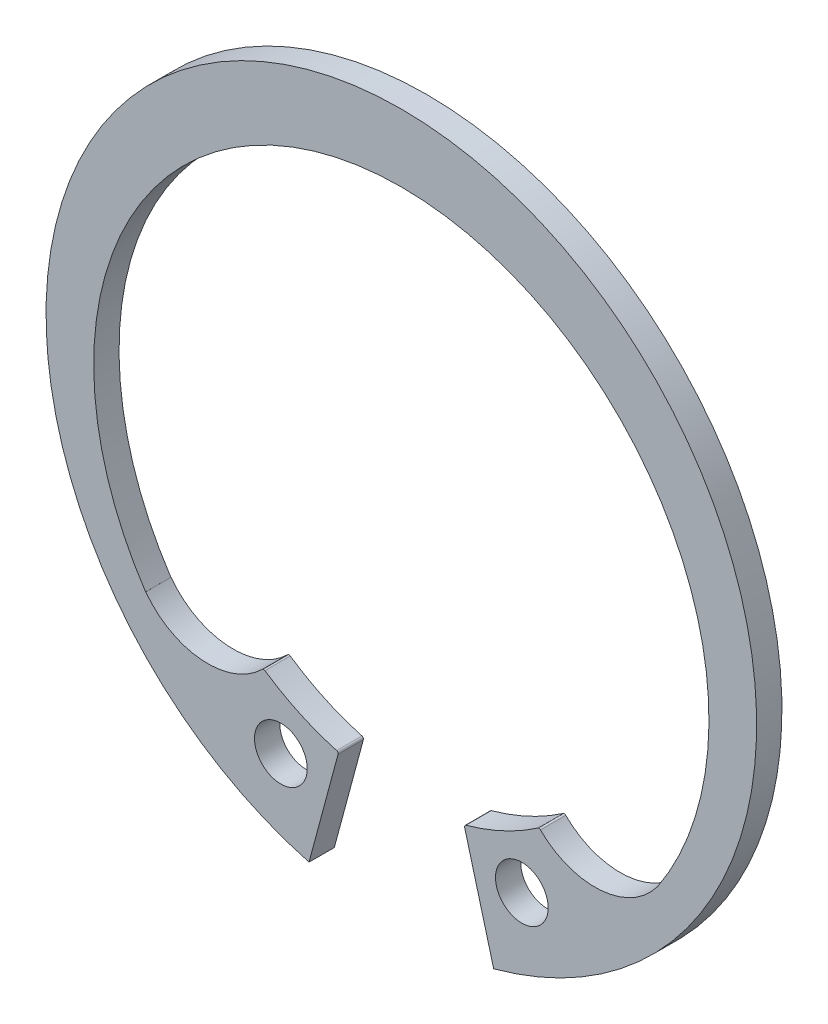
SolidWorks part; units mm, degrees
extrude "Body" add sketch "BodySke" against normal blind 1.2
sketch "BodySke" plane through (0, 0, 0) normal (0, 0, 1) x (1, 0, 0)
  line L0 (-1.5431, 0) -> (1.5431, 0) construction
  line L1 (0, 0) -> (0, 13.65) construction
  line L2 (4.3788, -16.2711) -> (3.5174, -13.0701)
  line L3 (-4.3788, -16.2711) -> (-3.5174, -13.0701)
  line L4 (0, 0) -> (11.6973, -12.1283) construction
  line L5 (0, 0) -> (-11.6973, -12.1283) construction
  line L6 (-5.3894, -11.2719) -> (-6.039, -13.686) construction
  line L7 (5.5192, -11.7541) -> (5.9093, -13.2037) construction
  arc A0 (-3.5174, -13.0701) -> (-7.3598, -10.9081) centre (-5.7142, -12.4789) ccw
  arc A1 (7.3598, -10.9081) -> (3.5174, -13.0701) centre (5.7142, -12.4789) ccw
  arc A2 (10.5866, -10.9766) -> (-10.5866, -10.9766) centre (0, -0.9388) ccw construction
  arc A3 (4.3788, -16.2711) -> (-4.3788, -16.2711) centre (0, 0) ccw
  circle A4 centre (5.7142, -12.4789) radius 1.25
  circle A5 centre (-5.7142, -12.4789) radius 1.25
  circle A6 centre (5.7142, -12.4789) radius 2.275 construction
  arc A7 (10.6692, -10.8888) -> (-10.6692, -10.8888) centre (0, -0.9388) ccw
  arc A8 (-5.7142, -12.4789) -> (5.7142, -12.4789) centre (0, 0) ccw construction
  arc A9 (-10.6692, -10.8888) -> (-7.3598, -10.9081) centre (-9.0054, -9.3372) ccw
  arc A10 (7.3598, -10.9081) -> (10.6692, -10.8888) centre (9.0054, -9.3372) ccw
  dimension "HoleDia" = 2.5
ref_plane "Plane1" through (0, 0, 0) normal (0, 0, 1) x (1, 0, 0)
ref_plane "Plane2" through (0, 0, 0) normal (0, 1, 0) x (1, 0, 0)
ref_plane "Plane3" through (0, 0, 0) normal (1, 0, 0) x (0, 0, -1)
sketch "Clipboard" plane through (0, 0, 0) normal (0, 0, 1) x (1, 0, 0)
  line L0 (0, 0) -> (3.2, 0)
  line L1 (0, 0) -> (0, 1.6)
  line L2 (0, 0) -> (0, -5.4)
  circle A0 centre (0, 0) radius 1.25
  circle A1 centre (0, 0) radius 16
  dimension "HoleDia" = 2.5
sketch "ModLugSke" plane through (0, 0, 0) normal (0, 0, 1) x (1, 0, 0)
  line L0 (4.3788, -16.2711) -> (3.0014, -11.1528)
  line L1 (-4.3788, -16.2711) -> (-3.0014, -11.1528)
  line L2 (9.1782, -6.8457) -> (13.5068, -10.0742) construction
  line L3 (-9.1782, -6.8457) -> (-13.5068, -10.0742) construction
  line L4 (-4.3788, -16.2711) -> (-3.5174, -13.0701) construction
  line L5 (3.5174, -13.0701) -> (4.3788, -16.2711) construction
  line L6 (0, 0) -> (0, -18.0732) construction
  line L7 (12.1234, -9.0423) -> (13.5068, -10.0742)
  line L8 (-13.5068, -10.0742) -> (-12.1234, -9.0423)
  arc A0 (4.3788, -16.2711) -> (13.5068, -10.0742) centre (0, 0) ccw
  arc A1 (-6.4688, -9.4476) -> (-3.0711, -11.0304) centre (0, 0) ccw
  arc A2 (4.3788, -16.2711) -> (-4.3788, -16.2711) centre (0, 0) ccw construction
  arc A3 (7.3598, -10.9081) -> (3.5174, -13.0701) centre (5.7142, -12.4789) ccw construction
  arc A4 (-6.4688, -9.4476) -> (-6.5956, -9.459) centre (-6.5253, -9.5301) ccw
  arc A5 (-12.1234, -9.0423) -> (-6.5956, -9.459) centre (-9.1782, -6.8457) ccw
  arc A6 (10.6692, -10.8888) -> (-10.6692, -10.8888) centre (0, -0.9388) ccw construction
  arc A7 (6.5956, -9.459) -> (12.1234, -9.0423) centre (9.1782, -6.8457) ccw
  arc A8 (3.0711, -11.0304) -> (6.4688, -9.4476) centre (0, 0) ccw
  arc A9 (-13.5068, -10.0742) -> (-4.3788, -16.2711) centre (0, 0) ccw
  circle A10 centre (-5.7142, -12.4789) radius 1.25
  circle A11 centre (-5.7142, -12.4789) radius 1.25 construction
  circle A12 centre (5.7142, -12.4789) radius 1.25
  circle A13 centre (5.7142, -12.4789) radius 1.25 construction
  arc A14 (-3.0711, -11.0304) -> (-3.0014, -11.1528) centre (-3.0979, -11.1268) cw
  arc A15 (3.0711, -11.0304) -> (3.0014, -11.1528) centre (3.0979, -11.1268) ccw
  arc A16 (6.4688, -9.4476) -> (6.5956, -9.459) centre (6.5253, -9.5301) cw
  point P43 (2.9755, -11.0566)
  dimension "D1" = 0.1
extrude "ModLug" add sketch "ModLugSke" against normal through all
sketch "UnlSke" [suppressed] plane through (0, 0, 0) normal (0, 0, 1) x (1, 0, 0)
  line L0 (2.1178, -8.3352) -> (3.2259, -12.6966)
  line L1 (-2.1178, -8.3352) -> (-3.2259, -12.6966)
  line L2 (-3.2259, -12.6966) -> (-2.1422, -8.4315) construction
  line L3 (2.1422, -8.4315) -> (3.2259, -12.6966) construction
  arc A0 (2.1178, -8.3352) -> (-2.1178, -8.3352) centre (0, 0) ccw
  arc A1 (3.2259, -12.6966) -> (-3.2259, -12.6966) centre (0, 0) ccw
  arc A2 (3.2259, -12.6966) -> (-3.2259, -12.6966) centre (0, 0) ccw construction
  circle A4 centre (-4.4431, -9.5688) radius 1
  circle A5 centre (4.4431, -9.5688) radius 1
  circle A6 centre (4.4431, -9.5688) radius 1 construction
  circle A7 centre (-4.4431, -9.5688) radius 1 construction
  arc A8 (2.2134, -8.3103) -> (4.9183, -7.0548) centre (0, 0) ccw construction
extrude "Unlug" [suppressed] add sketch "UnlSke" against normal through all
equation "' \"BoreDia@Clipboard\" = 8"
equation "' \"Thickness@Body\" = 0.8"
equation "' \"GrooveDia@BodySke\" = 8.4"
equation "' \"LugSection@Clipboard\" = 2.4"
equation "' \"LargeSection@Clipboard\" = 1.1"
equation "' \"HoleDia@Clipboard\" = 1.0"
equation "' \"BoreDia@Clipboard\" = 25"
equation "' \"Thickness@Body\" = 1.2"
equation "' \"GrooveDia@BodySke\" = 26.2"
equation "' \"LugSection@Clipboard\" = 4.5"
equation "' \"LargeSection@Clipboard\" = 2.7"
equation "' \"HoleDia@Clipboard\" = 2"
equation "\"SmallSection@Clipboard\" = \"LargeSection@Clipboard\" * 0.5"
equation "\"TipRad@BodySke\" = (\"LugSection@Clipboard\" - (\"GrooveDia@BodySke\" / 2  -  \"BoreDia@Clipboard\" / 2 ) ) / 2"
equation "\"HoleOffsetRad@BodySke\" = (\"GrooveDia@BodySke\" / 2) - \"LugSection@Clipboard\"  + \"TipRad@BodySke\""
equation "\"LargeRad@BodySke\" =  \"GrooveDia@BodySke\" / 2 -  \"LargeSection@Clipboard\""
equation "\"SmallRad@BodySke\" =  \"GrooveDia@BodySke\" / 2 -  \"SmallSection@Clipboard\""
equation "\"HoleDia@BodySke\" =  \"HoleDia@Clipboard\""
equation "\"FilletRad@BodySke\" = \"TipRad@BodySke\" * 1.0"
equation "\"GapAngle@BodySke\" = 360 - 0.965 * 360 * ( \"BoreDia@Clipboard\" /  \"GrooveDia@BodySke\")"
equation "\"LugAng@ModLugSke\" = \"GapAngle@BodySke\"  + 2 * 360 * (\"LugSection@Clipboard\" / (\"BoreDia@Clipboard\" * 3.1416))"
